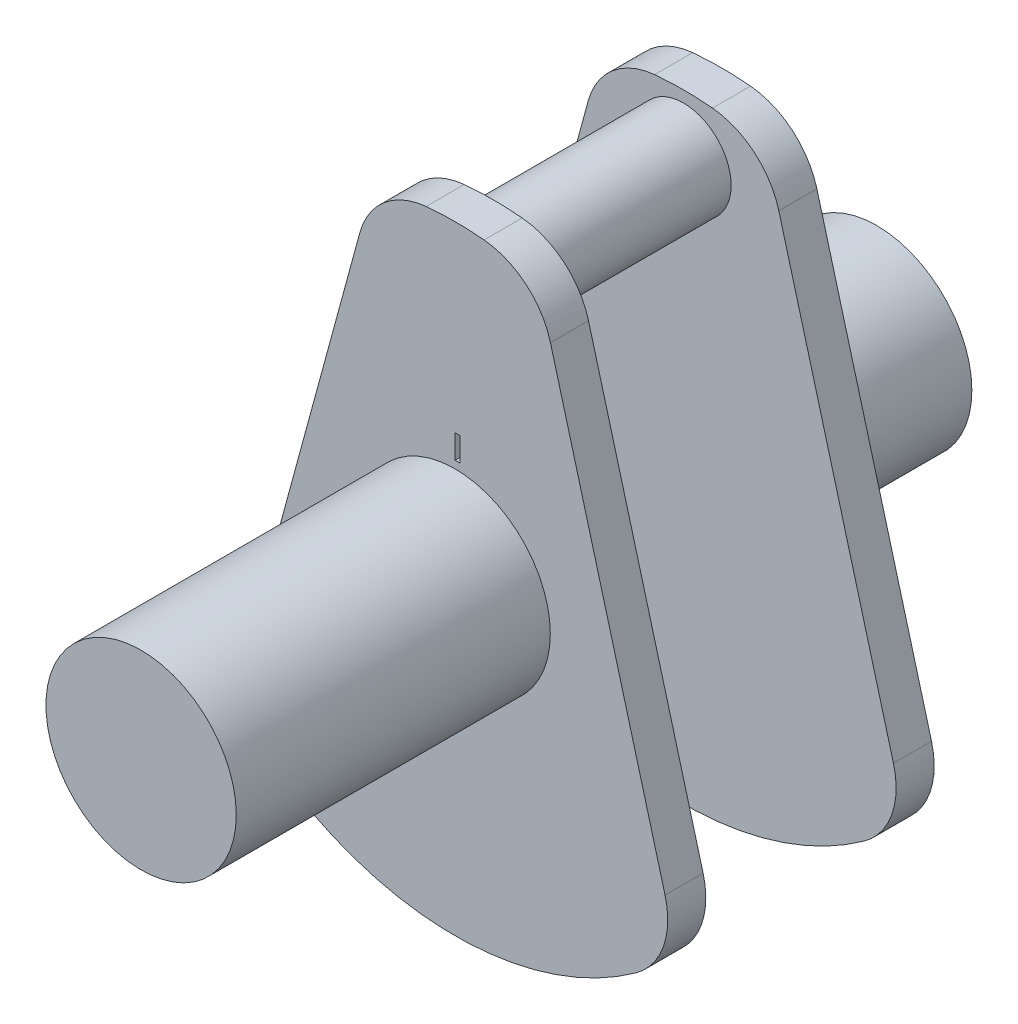
SolidWorks part; units mm, degrees
ref_plane "Front Plane" through (0, 0, 0) normal (0, 0, 1) x (1, 0, 0)
ref_plane "Top Plane" through (0, 0, 0) normal (0, 1, 0) x (1, 0, 0)
ref_plane "Right Plane" through (0, 0, 0) normal (1, 0, 0) x (0, 0, -1)
sketch "Sketch1" plane through (0, 0, 0) normal (0, 0, 1) x (1, 0, 0)
  line L0 (0, 165.1) -> (0, -165.1) construction
  line L1 (-50.8722, 134.5852) -> (-112.0614, -90.2408)
  line L2 (50.8722, 134.5852) -> (112.0614, -90.2408)
  arc A0 (-96.6349, -133.8645) -> (96.6349, -133.8645) centre (0, 0) ccw
  arc A1 (15.4655, 164.3741) -> (-15.4655, 164.3741) centre (0, 0) ccw
  arc A2 (50.8722, 134.5852) -> (15.4655, 164.3741) centre (11.6586, 123.9127) ccw
  arc A3 (-50.8722, 134.5852) -> (-15.4655, 164.3741) centre (-11.6586, 123.9127) cw
  arc A4 (112.0614, -90.2408) -> (96.6349, -133.8645) centre (72.8478, -100.9133) cw
  arc A5 (-112.0614, -90.2408) -> (-96.6349, -133.8645) centre (-72.8478, -100.9133) ccw
  point P10 (44.208, 159.0712)
  point P13 (-44.208, 159.0712)
  point P16 (118.7256, -114.7268)
  point P19 (-118.7256, -114.7268)
  dimension "D1" = 330.2
  dimension "D4" = 40.64
  dimension "D5" = 40.64
  dimension "D2" = 30.45
  dimension "D3" = 23.3172
extrude "Boss-Extrude1" add sketch "Sketch1" along normal blind 20.32
sketch "Sketch2" plane through (0, 0, 20.32) normal (0, 0, 1) x (1, 0, 0)
  line L0 (0, 165.1) -> (0, 133.5786) construction
  arc A0 (15.4655, 164.3741) -> (-15.4655, 164.3741) centre (0, 0) ccw construction
  circle A1 centre (0, 133.5786) radius 25.4
  dimension "D1" = 50.8
  dimension "D2" = 133.5786
extrude "Boss-Extrude2" add sketch "Sketch2" along normal blind 50.8
sketch "Sketch4" plane through (0, 0, 0) normal (0, 0, -1) x (-1, 0, 0)
  circle A0 centre (0, 0) radius 50.8
  dimension "D1" = 101.6
extrude "Boss-Extrude3" add sketch "Sketch4" along normal blind 82.804
mirror "Mirror1" about plane through (0, 133.5786, 71.12) normal (0, 0, 1) of bodies 103
sketch "Sketch5" plane through (0, 0, 225.044) normal (0, 0, 1) x (1, 0, 0)
  circle A0 centre (0, 0) radius 50.8 construction
  circle A1 centre (0, 0) radius 50.8
extrude "Boss-Extrude4" add sketch "Sketch5" along normal blind 84.836
sketch "Sketch6" plane through (0, 0, 142.24) normal (0, 0, 1) x (1, 0, 0)
  line L0 (0, 0) -> (0, 155.6807) construction
  line L2 (0, 67.4987) -> (2.54, 67.4987)
  line L3 (0, 67.4987) -> (0, 54.7987)
  line L4 (0, 54.7987) -> (2.54, 54.7987)
  line L5 (2.54, 67.4987) -> (2.54, 54.7987)
  point P7 (2.54, 54.7987)
  dimension "D1" = 2.54
  dimension "D2" = 12.7
extrude "Cut-Extrude1" cut sketch "Sketch6" against normal blind 2.54
